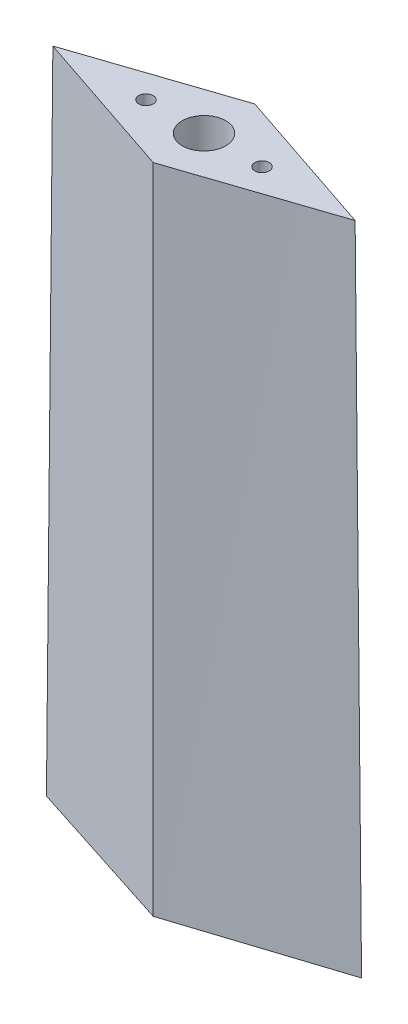
SolidWorks part; units mm, degrees
ref_plane "Front Plane" through (0, 0, 0) normal (0, 0, 1) x (1, 0, 0)
ref_plane "Top Plane" through (0, 0, 0) normal (0, 1, 0) x (1, 0, 0)
ref_plane "Right Plane" through (0, 0, 0) normal (1, 0, 0) x (0, 0, -1)
sketch "Sketch1" plane through (0, 0, 0) normal (0, 0, 1) x (1, 0, 0)
  line L0 (142.4212, 465.168) -> (219.716, 465.168)
  line L1 (219.716, 465.168) -> (213.5025, 1096.9676)
  line L2 (213.5025, 1096.9676) -> (181.0686, 1174.3372)
  line L3 (181.0686, 1174.3372) -> (148.6348, 1096.9676)
  line L4 (148.6348, 1096.9676) -> (142.4212, 465.168)
  point P2 (181.0686, 465.168)
extrude "Boss-Extrude1" add sketch "Sketch1" along normal blind 11.1125 and the other way blind 11.1125
sketch "Sketch2" plane through (0, 465.168, 0) normal (0, -1, 0) x (1, 0, 0)
  line L0 (142.4212, 0) -> (181.0686, 11.1125)
  line L1 (142.4212, -11.1125) -> (142.4212, 11.1125) construction
  line L2 (142.4212, 11.1125) -> (219.716, 11.1125) construction
  line L3 (181.0686, 11.1125) -> (219.716, 0)
  line L4 (219.716, -11.1125) -> (219.716, 11.1125) construction
  line L8 (142.4212, 0) -> (137.8486, 0)
  line L9 (137.8486, 0) -> (137.8486, 15.2584)
  line L10 (137.8486, 15.2584) -> (222.7051, 15.2584)
  line L11 (222.7051, 15.2584) -> (222.7051, 0)
  line L12 (222.7051, 0) -> (219.716, 0)
ref_plane "Plane1" through (0, 1096.9676, 0) normal (0, 1, 0) x (1, 0, 0)
sketch "Sketch3" plane through (0, 1096.9676, 0) normal (0, 1, 0) x (1, 0, 0)
  line L1 (148.6348, 11.1125) -> (148.6348, -11.1125) construction
  line L3 (213.5025, 11.1125) -> (213.5025, -11.1125) construction
  line L4 (213.5025, 0) -> (181.0686, -11.1125)
  line L5 (181.0686, -11.1125) -> (148.6348, 0)
  line L6 (148.6348, 0) -> (137.8486, 0)
  line L7 (137.8486, 0) -> (137.8486, -15.2584)
  line L8 (137.8486, -15.2584) -> (222.7051, -15.2584)
  line L9 (222.7051, -15.2584) -> (222.7051, 0)
  line L10 (222.7051, 0) -> (213.5025, 0)
loft "Cut-Loft1" cut profiles "Sketch2", "Sketch3"
mirror "Mirror1" about plane through (0, 0, 0) normal (0, 0, 1) of "Cut-Loft1"
ref_plane "Plane2" through (-32.1031, 13.4578, 93.6987) normal (-0.3212, 0.1346, 0.9374) x (0.947, 0.0457, 0.3179)
sketch "Sketch5" plane through (-32.1031, 13.4578, 93.6987) normal (-0.3212, 0.1346, 0.9374) x (0.947, 0.0457, 0.3179)
  line L1 (164.4105, 1280.8293) -> (274.288, 1280.8293)
  line L2 (164.4105, 1280.8293) -> (164.4105, 997.7782)
  line L3 (164.4105, 997.7782) -> (274.288, 997.7782)
  line L4 (274.288, 1280.8293) -> (274.288, 997.7782)
extrude "Cut-Extrude2" cut sketch "Sketch5" along normal through all
ref_plane "Plane3" through (69.4583, 29.1174, 202.7265) normal (0.3212, 0.1346, 0.9374) x (0.947, -0.0457, -0.3179)
sketch "Sketch6" plane through (69.4583, 29.1174, 202.7265) normal (0.3212, 0.1346, 0.9374) x (0.947, -0.0457, -0.3179)
  line L1 (57.1921, 1173.3831) -> (206.3136, 1173.3831)
  line L2 (57.1921, 1173.3831) -> (57.1921, 1064.4614)
  line L3 (57.1921, 1064.4614) -> (206.3136, 1064.4614)
  line L4 (206.3136, 1173.3831) -> (206.3136, 1064.4614)
extrude "Cut-Extrude3" cut sketch "Sketch6" along normal through all
mirror "Mirror2" about plane through (0, 0, 0) normal (0, 0, 1) of "Cut-Extrude2", "Cut-Extrude3"
sketch "Sketch7" plane through (0, 465.168, 0) normal (0, -1, 0) x (1, 0, 0)
  circle A0 centre (181.0686, 0) radius 4.7625
  dimension "D1" = 9.525
extrude "Cut-Extrude4" cut sketch "Sketch7" against normal blind 635
sketch "Sketch8" plane through (0, 0, 0) normal (0, 0, 1) x (1, 0, 0)
  line L0 (105.7103, 602.8372) -> (255.485, 602.8372)
  line L1 (105.7103, 1207.5881) -> (255.485, 1207.5881)
  line L2 (105.7103, 1207.5881) -> (105.7103, 454.0044)
  line L3 (105.7103, 454.0044) -> (255.485, 454.0044)
  line L4 (255.485, 1207.5881) -> (255.485, 454.0044)
  line L5 (255.485, 745.7122) -> (105.7103, 745.7122)
  line L6 (105.7103, 888.5872) -> (255.485, 888.5872)
  line L7 (255.485, 1031.4622) -> (105.7103, 1031.4622)
  dimension "D1" = 142.875
  dimension "D2" = 142.875
  dimension "D3" = 142.875
  dimension "D4" = 142.875
extrude "Cut-Extrude8" cut sketch "Sketch8" against normal through all and the other way through all contours L4 L0 L2 L3 | L7 L4 L1 L2 | L4 L5 L2 L0 | L6 L2 L5 L4
sketch "Sketch15" plane through (0, 888.5872, 0) normal (0, -1, 0) x (1, 0, 0)
  circle A0 centre (168.3686, 0) radius 1.5875
  circle A1 centre (193.7686, 0) radius 1.5875
  circle A2 centre (181.0686, 0) radius 4.7625 construction
  dimension "D1" = 12.7
  dimension "D2" = 12.7
  dimension "D3" = 3.175
extrude "Cut-Extrude13" cut sketch "Sketch15" against normal blind 12.7
sketch "Sketch16" plane through (0, 1031.4622, 0) normal (0, 1, 0) x (1, 0, 0)
  circle A0 centre (168.3686, 0) radius 1.5875
  circle A1 centre (193.7686, 0) radius 1.5875
  circle A2 centre (181.0686, 0) radius 4.7625 construction
  dimension "D1" = 12.7
  dimension "D2" = 12.7
  dimension "D3" = 3.175
extrude "Cut-Extrude14" cut sketch "Sketch16" against normal blind 12.7
